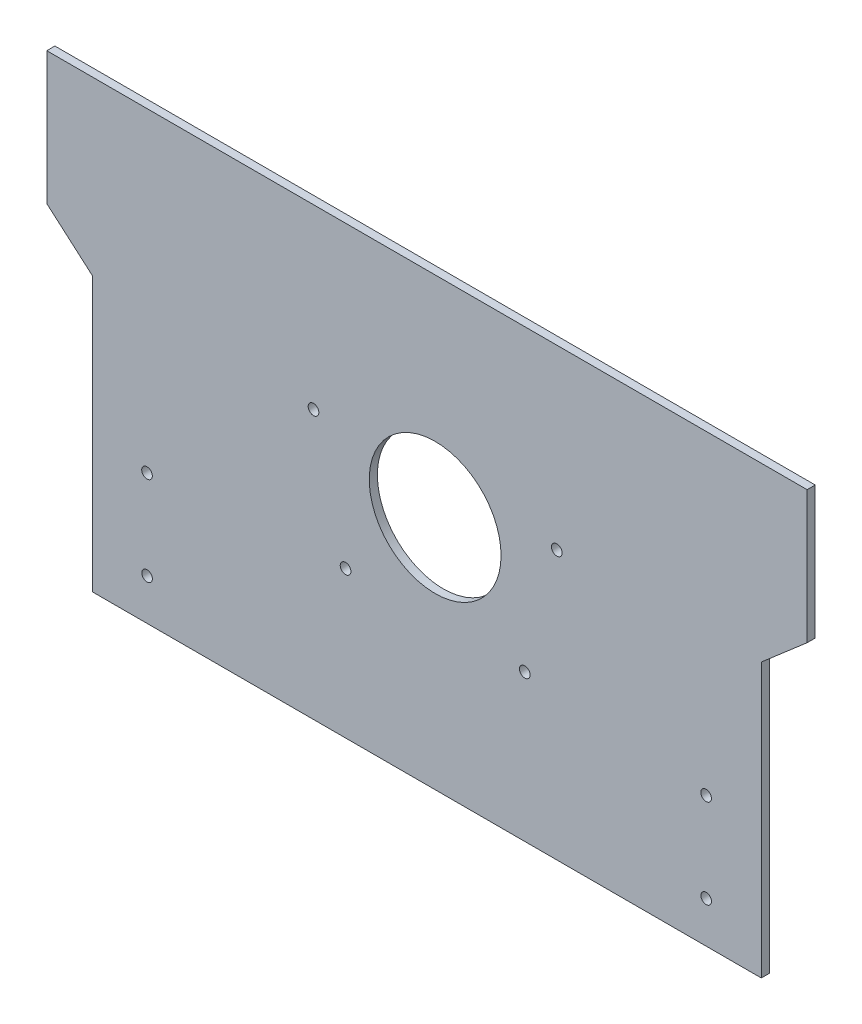
SolidWorks part; units mm, degrees
ref_plane "Front Plane" through (0, 0, 0) normal (0, 0, 1) x (1, 0, 0)
ref_plane "Top Plane" through (0, 0, 0) normal (0, 1, 0) x (1, 0, 0)
ref_plane "Right Plane" through (0, 0, 0) normal (1, 0, 0) x (0, 0, -1)
sketch "Sketch1" plane through (0, 0, 0) normal (0, 0, 1) x (1, 0, 0)
  line L0 (72.39, -58.58) -> (72.4, -84.71)
  line L1 (72.4, -84.71) -> (81.44, -92.56)
  line L2 (81.44, -92.56) -> (81.43, -146.54)
  line L3 (81.43, -146.54) -> (213.35, -146.53)
  line L4 (213.35, -146.53) -> (213.35, -92.55)
  line L5 (213.35, -92.55) -> (222.39, -84.73)
  line L6 (222.39, -84.73) -> (222.39, -58.58)
  line L7 (222.39, -58.58) -> (72.39, -58.58)
  circle A0 centre (149.01, -100.02) radius 13
  circle A1 centre (202.46, -120.78) radius 1.05
  circle A2 centre (202.48, -138.37) radius 1.05
  circle A3 centre (92.18, -138.41) radius 1.044
  circle A4 centre (92.17, -120.83) radius 1.05
  circle A5 centre (131.334, -117.57) radius 1.05
  circle A6 centre (166.686, -117.57) radius 1.05
  circle A7 centre (173.01, -93.57) radius 1.05
  circle A8 centre (125.01, -93.57) radius 1.05
extrude "Boss-Extrude1" add sketch "Sketch1" along normal blind 1.6
